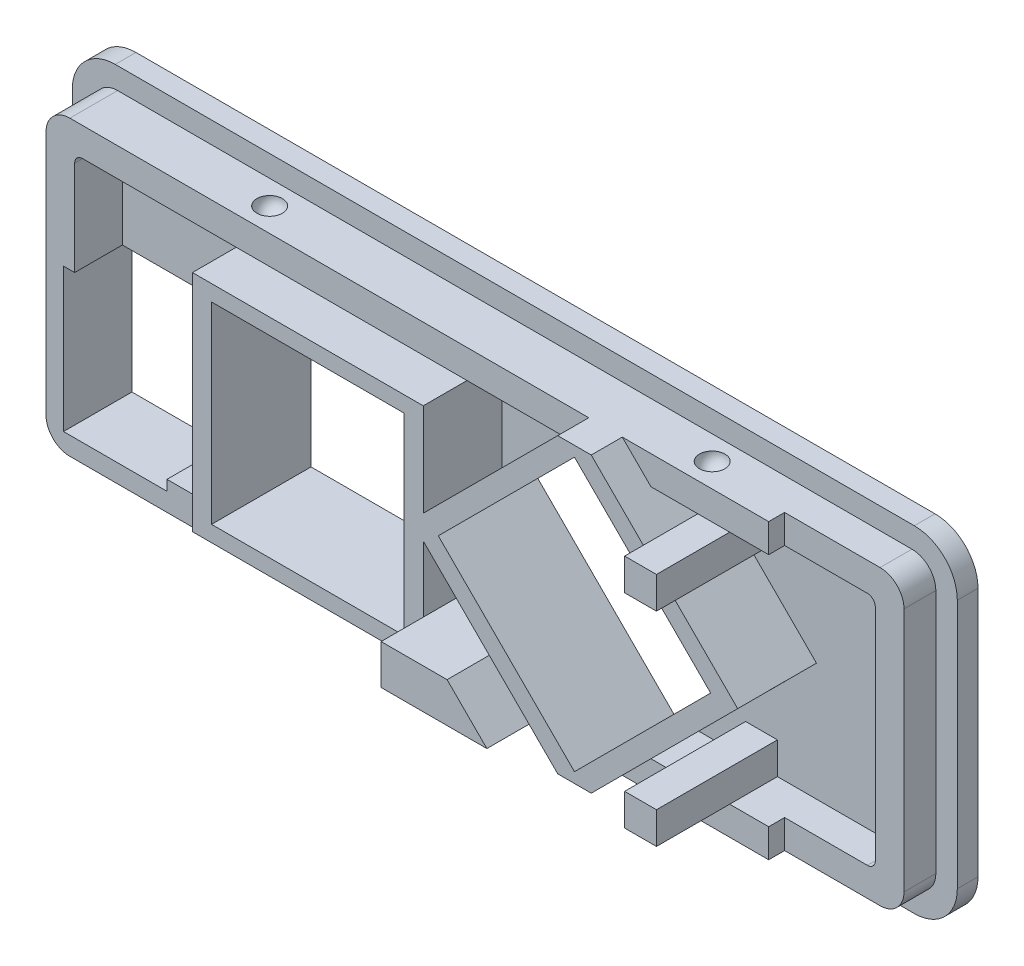
SolidWorks part; units mm, degrees
material "PLA"
ref_plane "Front Plane" through (0, 0, 0) normal (0, 0, 1) x (1, 0, 0)
ref_plane "Top Plane" through (0, 0, 0) normal (0, 1, 0) x (1, 0, 0)
ref_plane "Right Plane" through (0, 0, 0) normal (1, 0, 0) x (0, 0, -1)
sketch "Sketch1" plane through (0, 0, 0) normal (0, 0, 1) x (1, 0, 0)
  line L1 (2.7, 0) -> (52.9, 0)
  line L2 (0, 2.7) -> (0, 18.4)
  line L3 (2.7, 21.1) -> (52.9, 21.1)
  line L4 (55.6, 2.7) -> (55.6, 18.4)
  arc A0 (52.9, 0) -> (55.6, 2.7) centre (52.9, 2.7) ccw
  arc A1 (2.7, 0) -> (0, 2.7) centre (2.7, 2.7) cw
  arc A2 (0, 18.4) -> (2.7, 21.1) centre (2.7, 18.4) cw
  arc A3 (52.9, 21.1) -> (55.6, 18.4) centre (52.9, 18.4) cw
  point P9 (0, 0)
  dimension "D1" = 2.7
  dimension "D2" = 50.2
  dimension "D3" = 15.7
extrude "Boss-Extrude1" add sketch "Sketch1" along normal blind 1.3
sketch "Sketch4" plane through (0, 0, 1.3) normal (0, 0, 1) x (1, 0, 0)
  line L11 (54.25, 2.7) -> (54.25, 18.4)
  line L12 (52.9, 19.75) -> (2.7, 19.75)
  line L13 (1.35, 18.4) -> (1.35, 2.7)
  line L14 (2.7, 1.35) -> (52.9, 1.35)
  line L15 (54.25, 2.85) -> (54.25, 18.25)
  line L16 (52.75, 19.75) -> (2.85, 19.75)
  line L17 (1.35, 18.25) -> (1.35, 2.85)
  line L18 (2.85, 1.35) -> (52.75, 1.35)
  arc A4 (54.25, 18.25) -> (52.75, 19.75) centre (52.75, 18.25) ccw
  arc A5 (54.25, 2.85) -> (52.75, 1.35) centre (52.75, 2.85) cw
  arc A6 (1.35, 2.85) -> (2.85, 1.35) centre (2.85, 2.85) ccw
  arc A7 (2.85, 19.75) -> (1.35, 18.25) centre (2.85, 18.25) ccw
  arc A8 (52.9, 1.35) -> (54.25, 2.7) centre (52.9, 2.7) ccw
  arc A10 (54.25, 18.4) -> (52.9, 19.75) centre (52.9, 18.4) ccw
  arc A12 (2.7, 19.75) -> (1.35, 18.4) centre (2.7, 18.4) ccw
  arc A14 (1.35, 2.7) -> (2.7, 1.35) centre (2.7, 2.7) ccw
  dimension "D2" = 1.5
  dimension "D1" = 1.35
extrude "Boss-Extrude3" add sketch "Sketch4" along normal blind 3
sketch "Sketch5" plane through (0, 0, 4.3) normal (0, 0, 1) x (1, 0, 0)
  line L8 (52.45, 17.95) -> (3.15, 17.95)
  line L9 (3.15, 17.95) -> (3.15, 3.15)
  line L10 (3.15, 3.15) -> (52.45, 3.15)
  line L11 (52.45, 3.15) -> (52.45, 17.95)
  line L12 (51.95, 17.95) -> (3.65, 17.95)
  line L13 (3.15, 17.45) -> (3.15, 3.65)
  line L14 (3.65, 3.15) -> (51.95, 3.15)
  line L15 (52.45, 3.65) -> (52.45, 17.45)
  arc A4 (51.95, 3.15) -> (52.45, 3.65) centre (51.95, 3.65) ccw
  arc A5 (51.95, 17.95) -> (52.45, 17.45) centre (51.95, 17.45) cw
  arc A6 (3.65, 17.95) -> (3.15, 17.45) centre (3.65, 17.45) ccw
  arc A7 (3.15, 3.65) -> (3.65, 3.15) centre (3.65, 3.65) ccw
  dimension "D2" = 0.5
  dimension "D1" = 1.8
extrude "Cut-Extrude1" cut sketch "Sketch5" against normal blind 3
sketch "Sketch10" plane through (0, 19.75, 0) normal (0, 1, 0) x (1, 0, 0)
  line L0 (41.7, -2) -> (41.7, -3.6)
  line L1 (41.7, -3.6) -> (42.6713, -3.8888)
  line L3 (52.75, -1.3) -> (2.85, -1.3) construction
  line L4 (55.6, -1.3) -> (55.6, 0) construction
  arc A0 (41.7, -2) -> (41.7, -3.6) centre (41.7, -2.8) ccw
  dimension "D2" = 0.8
  dimension "D1" = 1.6
  dimension "D3" = 1.5
  dimension "D4" = 13.9
revolve "Cut-Revolve1" cut sketch "Sketch10" angle 360 about L0
ref_plane "Plane1" through (0, 10.55, 0) normal (0, -1, 0) x (-1, 0, 0)
mirror "Mirror1" about plane through (0, 10.55, 0) normal (0, -1, 0) of "Cut-Revolve1"
sketch "Sketch11" plane through (0, 0, 0) normal (0, 0, -1) x (-1, 0, 0)
  line L0 (0, 18.4) -> (0, 2.7) construction
  line L1 (-2.45, 2.5) -> (-8.95, 2.5)
  line L2 (-2.45, 2.5) -> (-2.45, 11.5)
  line L3 (-2.45, 11.5) -> (-8.95, 11.5)
  line L4 (-8.95, 2.5) -> (-8.95, 11.5)
  line L5 (-2.45, 2.5) -> (-8.95, 11.5) construction
  line L6 (-2.45, 11.5) -> (-8.95, 2.5) construction
  line L8 (-2.7, 0) -> (-52.9, 0) construction
  point P0 (-5.7, 7)
  dimension "D1" = 5.7
  dimension "D2" = 2.5
  dimension "D3" = 9
  dimension "D4" = 6.5
extrude "Cut-Extrude2" cut sketch "Sketch11" against normal blind 4.3
sketch "Sketch12" plane through (0, 0, 0) normal (0, 0, -1) x (-1, 0, 0)
  line L1 (-25.8, 16.15) -> (-13.7, 16.15)
  line L2 (-25.8, 16.15) -> (-25.8, 4.05)
  line L3 (-25.8, 4.05) -> (-13.7, 4.05)
  line L4 (-13.7, 16.15) -> (-13.7, 4.05)
  line L5 (-25.8, 16.15) -> (-13.7, 4.05) construction
  line L6 (-25.8, 4.05) -> (-13.7, 16.15) construction
  line L7 (-52.9, 21.1) -> (-2.7, 21.1) construction
  line L9 (0, 18.4) -> (0, 2.7) construction
  point P0 (-19.75, 10.1)
  dimension "D1" = 11
  dimension "D2" = 19.75
  dimension "D3" = 12.1
  dimension "D4" = 12.1
sketch "Sketch13" plane through (0, 0, 0) normal (0, 0, -1) x (-1, 0, 0)
  line L0 (-45.056, 10.55) -> (-36.5, 1.994)
  line L1 (-45.056, 10.55) -> (-36.5, 19.106)
  line L2 (-36.5, 1.994) -> (-27.944, 10.55)
  line L3 (-36.5, 19.106) -> (-27.944, 10.55)
  line L4 (-45.056, 10.55) -> (-27.944, 10.55) construction
  line L5 (-36.5, 1.994) -> (-36.5, 19.106) construction
  line L6 (-0.715, 10.55) -> (0.715, 10.55) construction
  line L7 (-52.9, 21.1) -> (-2.7, 21.1) construction
  line L10 (0, 18.4) -> (0, 2.7) construction
  point P1 (-36.5, 10.55)
  dimension "D1" = 0
  dimension "D2" = 10.55
  dimension "D3" = 12.1
  dimension "D5" = 36.5
extrude "Cut-Extrude4" cut sketch "Sketch12" against normal blind 1.3
sketch "Sketch17" plane through (0, 0, 0) normal (0, 0, -1) x (-1, 0, 0)
  line L8 (-13.7, 16.15) -> (-25.8, 16.15) construction
  line L9 (-27, 17.15) -> (-12.5, 17.15)
  line L10 (-27, 17.15) -> (-27, 3.05)
  line L11 (-27, 3.05) -> (-12.5, 3.05)
  line L12 (-12.5, 17.15) -> (-12.5, 3.05)
  line L13 (-25.8, 4.05) -> (-13.7, 4.05) construction
  line L14 (-13.7, 4.05) -> (-13.7, 16.15) construction
  line L15 (-25.8, 16.15) -> (-25.8, 4.05) construction
  line L17 (-13.7, 4.05) -> (-25.8, 4.05)
  line L18 (-13.7, 4.05) -> (-13.7, 16.15)
  line L19 (-13.7, 16.15) -> (-25.8, 16.15)
  line L20 (-25.8, 4.05) -> (-25.8, 16.15)
  dimension "D1" = 1
  dimension "D2" = 1
  dimension "D3" = 1.2
  dimension "D4" = 1.2
extrude "Boss-Extrude4" add sketch "Sketch17" against normal blind 6.25
extrude "Cut-Extrude5" cut sketch "Sketch13" against normal blind 4.3
sketch "Sketch18" plane through (0, 0, 0) normal (0, 0, -1) x (-1, 0, 0)
  line L18 (-36.5, 19.106) -> (-45.056, 10.55)
  line L19 (-45.056, 10.55) -> (-36.5, 1.994)
  line L20 (-36.5, 1.994) -> (-27.944, 10.55)
  line L21 (-27.944, 10.55) -> (-36.5, 19.106)
  line L22 (-46.753, 10.55) -> (-36.5, 0.297)
  line L23 (-36.5, 0.297) -> (-26.247, 10.55)
  line L24 (-26.247, 10.55) -> (-36.5, 20.803)
  line L25 (-36.5, 20.803) -> (-46.753, 10.55)
  line L26 (-46.753, 10.55) -> (-36.5, 0.297)
  line L27 (-36.5, 0.297) -> (-26.247, 10.55)
  line L28 (-26.247, 10.55) -> (-36.5, 20.803)
  line L29 (-36.5, 20.803) -> (-46.753, 10.55)
  dimension "D1" = 1.2
extrude "Boss-Extrude5" add sketch "Sketch18" against normal blind 6.25
sketch "Sketch20" plane through (0, 0, 4.3) normal (0, 0, 1) x (1, 0, 0)
  line L0 (35.447, 19.75) -> (37.553, 19.75)
  line L1 (35.447, 19.75) -> (2.85, 19.75) construction
  line L2 (52.75, 19.75) -> (37.553, 19.75) construction
  line L3 (37.553, 19.75) -> (36.5, 20.803)
  line L4 (36.5, 20.803) -> (35.447, 19.75)
extrude "Cut-Extrude6" cut sketch "Sketch20" against normal blind 3 and the other way blind 20
mirror "Mirror2" about plane through (0, 10.55, 0) normal (0, -1, 0) of "Cut-Extrude6"
sketch "Sketch21" plane through (0, 0, 0) normal (0, 0, -1) x (-1, 0, 0)
  line L0 (-52.9, 21.1) -> (-2.7, 21.1) construction
  line L1 (-30.25, 17.85) -> (-27.75, 17.85)
  line L2 (-30.25, 17.85) -> (-30.25, 15.35)
  line L3 (-30.25, 15.35) -> (-27.75, 15.35)
  line L4 (-27.75, 17.85) -> (-27.75, 15.35)
  line L5 (-30.25, 17.85) -> (-27.75, 15.35) construction
  line L6 (-30.25, 15.35) -> (-27.75, 17.85) construction
  line L7 (0, 18.4) -> (0, 2.7) construction
  point P0 (-29, 16.6)
  dimension "D1" = 4.5
  dimension "D2" = 2.5
  dimension "D3" = 2.5
  dimension "D4" = 29
extrude "Cut-Extrude7" cut sketch "Sketch21" against normal blind 10
ref_plane "Plane2" through (27.8, 0, 0) normal (-1, 0, 0) x (0, 0, 1)
mirror "Mirror3" about plane through (27.8, 0, 0) normal (-1, 0, 0) of "Mirror1", "Cut-Revolve1"
sketch "Sketch24" plane through (0, 0, 1.3) normal (0, 0, 1) x (1, 0, 0)
  line L0 (33.647, 3.15) -> (27, 3.15)
  line L2 (27, 3.15) -> (27, 5.65)
  line L4 (27, 5.65) -> (31.147, 5.65)
  line L5 (27, 9.797) -> (33.647, 3.15) construction
  line L6 (31.147, 5.65) -> (33.647, 3.15)
  line L7 (8.95, 3.15) -> (12.5, 3.15) construction
  line L8 (27, 11.303) -> (27, 17.15) construction
  dimension "D1" = 2.5
extrude "Boss-Extrude7" add sketch "Sketch24" along normal blind 7.6
sketch "Sketch25" plane through (0, 0, 1.3) normal (0, 0, 1) x (1, 0, 0)
  line L1 (44.3, 3.15) -> (42.3, 3.15)
  line L2 (44.3, 3.15) -> (44.3, 5.15)
  line L3 (44.3, 5.15) -> (42.3, 5.15)
  line L4 (42.3, 3.15) -> (42.3, 5.15)
  line L6 (39.353, 3.15) -> (51.95, 3.15) construction
  line L7 (52.45, 3.65) -> (52.45, 17.45) construction
  dimension "D1" = 8.15
  dimension "D2" = 2
  dimension "D3" = 2
extrude "Boss-Extrude8" add sketch "Sketch25" along normal blind 7.6
mirror "Mirror4" about plane through (0, 10.55, 0) normal (0, -1, 0) of "Boss-Extrude8"
sketch "Sketch23" plane through (0, 0, 1.3) normal (0, 0, 1) x (1, 0, 0)
  line L0 (-0.715, 10.55) -> (0.715, 10.55) construction
  line L1 (48.7, 3.15) -> (46.3, 3.15)
  line L2 (48.7, 3.15) -> (48.7, 17.95)
  line L3 (48.7, 17.95) -> (46.3, 17.95)
  line L4 (46.3, 3.15) -> (46.3, 17.95)
  line L5 (48.7, 3.15) -> (46.3, 17.95) construction
  line L6 (48.7, 17.95) -> (46.3, 3.15) construction
  line L7 (39.353, 3.15) -> (42.3, 3.15) construction
  line L8 (51.95, 17.95) -> (44.3, 17.95) construction
  line L9 (0, 18.4) -> (0, 2.7) construction
  point P0 (47.5, 10.55)
  dimension "D1" = 2.4
  dimension "D2" = 47.5
extrude "Boss-Extrude6" [suppressed] add sketch "Sketch23" along normal blind 3
sketch "Sketch27" plane through (54.25, 0, 0) normal (1, 0, 0) x (0, 0, -1)
  line L0 (-4.3, 2.85) -> (-4.3, 18.25) construction
  line L2 (-3.3, 19.75) -> (-4.3, 19.75)
  line L3 (-3.3, 19.75) -> (-3.3, 1.35)
  line L4 (-3.3, 1.35) -> (-4.3, 1.35)
  line L5 (-4.3, 19.75) -> (-4.3, 1.35)
  line L6 (-3.3, 19.75) -> (-4.3, 1.35) construction
  line L7 (-3.3, 1.35) -> (-4.3, 19.75) construction
  point P2 (-4.3, 10.55)
  point P3 (-3.8, 10.55)
  dimension "D1" = 1
  dimension "D2" = 18.4
extrude "Cut-Extrude8" cut sketch "Sketch27" against normal blind 7.5
equation "\"OutterLength\"= 55.6mm"
equation "\"OutterWidth\"= 21.1mm"
equation "\"EdgeRadius\"= 2.7mm"
equation "\"LipOffset\"= 1.35mm"
equation "\"LipHeight\"= 3mm"
equation "\"LipThickness\"= 1.8mm"
equation "\"LatchRadius\"= 0.8mm"
equation "\"D2@Sketch1\"=\"OutterLength\"-\"EdgeRadius\"*2"
equation "\"D3@Sketch1\"=\"OutterWidth\"-\"EdgeRadius\"*2"
equation "\"D1@Sketch1\"=\"EdgeRadius\""
equation "\"D1@Sketch4\"=\"LipOffset\""
equation "\"LipRadius\"= 1.5mm"
equation "\"D2@Sketch4\"=\"LipRadius\""
equation "\"D1@Sketch5\"=\"LipThickness\""
equation "\"D1@Boss-Extrude3\"=\"LipHeight\""
equation "\"D1@Cut-Extrude1\"=\"LipHeight\""
equation "\"D2@Sketch10\"=\"LatchRadius\""
equation "\"D1@Sketch10\"=\"LatchRadius\"*2"
equation "\"D3@Sketch10\"=\"LipHeight\"/2"
equation "\"D1@Cut-Extrude2\"=\"LipHeight\"+\"WallThickness\""
equation "\"WallThickness\"= 1.3mm"
equation "\"D1@Boss-Extrude1\"=\"WallThickness\""
equation "\"D1@Cut-Extrude4\"=\"WallThickness\""
equation "\"D1@Cut-Extrude5\"=\"WallThickness\"+\"LipHeight\""
equation "\"D1@Cut-Extrude6\"=\"LipHeight\""
equation "\"D2@Cut-Extrude6\"=20mm"
equation "\"D4@Sketch10\"=\"OutterLength\"/4"
equation "\"D2@Sketch13\"=\"OutterWidth\"/2"
